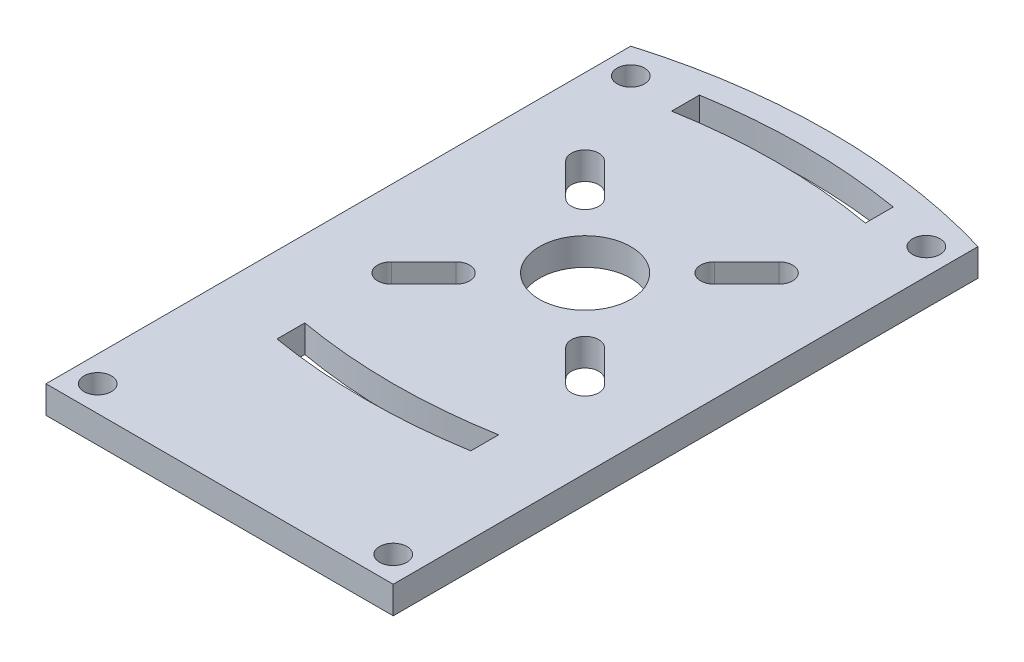
SolidWorks part; units mm, degrees
ref_plane "前视基准面" through (0, 0, 0) normal (0, 0, 1) x (1, 0, 0)
ref_plane "上视基准面" through (0, 0, 0) normal (0, 1, 0) x (1, 0, 0)
ref_plane "右视基准面" through (0, 0, 0) normal (1, 0, 0) x (0, 0, -1)
sketch "草图1" plane through (0, 0, 0) normal (0, 1, 0) x (1, 0, 0)
  line L0 (0, 0) -> (19, 0)
  line L1 (0, 0) -> (-19, 0)
  line L2 (-19, 0) -> (-19, 64)
  line L3 (19, 0) -> (19, 64)
  line L6 (10.6066, 19.9292) -> (10.6066, 16.885)
  line L7 (-7.0711, 47.0711) -> (-10.6066, 50.6066) construction
  line L8 (-8.1317, 46.0104) -> (-11.6673, 49.5459)
  line L9 (-6.0104, 48.1317) -> (-9.5459, 51.6673)
  line L10 (7.0711, 47.0711) -> (10.6066, 50.6066) construction
  line L11 (6.0104, 48.1317) -> (9.5459, 51.6673)
  line L12 (8.1317, 46.0104) -> (11.6673, 49.5459)
  line L13 (7.0711, 32.9289) -> (10.6066, 29.3934) construction
  line L14 (8.1317, 33.9896) -> (11.6673, 30.4541)
  line L15 (6.0104, 31.8683) -> (9.5459, 28.3327)
  line L16 (-7.0711, 32.9289) -> (-10.6066, 29.3934) construction
  line L17 (-6.0104, 31.8683) -> (-9.5459, 28.3327)
  line L18 (-8.1317, 33.9896) -> (-11.6673, 30.4541)
  line L19 (-10.6066, 60.0708) -> (-10.6066, 63.115)
  line L20 (10.6066, 60.0708) -> (10.6066, 63.115)
  line L21 (-10.6066, 19.9292) -> (-10.6066, 16.885)
  arc A0 (-19, 64) -> (19, 64) centre (0, 0) cw
  circle A1 centre (0, 40) radius 5
  arc A2 (-8.1317, 46.0104) -> (-6.0104, 48.1317) centre (-7.0711, 47.0711) ccw
  arc A3 (-9.5459, 51.6673) -> (-11.6673, 49.5459) centre (-10.6066, 50.6066) ccw
  arc A4 (6.0104, 48.1317) -> (8.1317, 46.0104) centre (7.0711, 47.0711) ccw
  arc A5 (11.6673, 49.5459) -> (9.5459, 51.6673) centre (10.6066, 50.6066) ccw
  arc A6 (8.1317, 33.9896) -> (6.0104, 31.8683) centre (7.0711, 32.9289) ccw
  arc A7 (9.5459, 28.3327) -> (11.6673, 30.4541) centre (10.6066, 29.3934) ccw
  arc A8 (-6.0104, 31.8683) -> (-8.1317, 33.9896) centre (-7.0711, 32.9289) ccw
  arc A9 (-11.6673, 30.4541) -> (-9.5459, 28.3327) centre (-10.6066, 29.3934) ccw
  arc A12 (10.6066, 63.115) -> (-10.6066, 63.115) centre (0, 0) ccw
  arc A13 (10.6066, 60.0708) -> (-10.6066, 60.0708) centre (0, 0) ccw
  arc A14 (10.6066, 19.9292) -> (-10.6066, 19.9292) centre (0, 80) cw
  arc A15 (10.6066, 16.885) -> (-10.6066, 16.885) centre (0, 80) cw
  circle A16 centre (-16.1716, 2.8284) radius 1.5
  circle A17 centre (-16.1716, 61.1716) radius 1.5
  circle A18 centre (16.1716, 61.1716) radius 1.5
  circle A19 centre (16.1716, 2.8284) radius 1.5
  point P9 (-8.8388, 48.8388)
  point P19 (8.8388, 48.8388)
  point P26 (8.8388, 31.1612)
  point P33 (-8.8388, 31.1612)
  point P40 (0, 40)
extrude "凸台-拉伸2" add sketch "草图1" along normal blind 3
